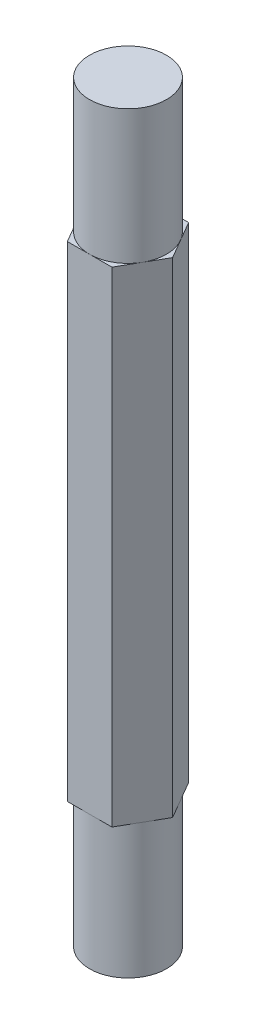
SolidWorks part; units mm, degrees
material "1060 Alloy"
ref_plane "Front Plane" through (0, 0, 0) normal (0, 0, 1) x (1, 0, 0)
ref_plane "Top Plane" through (0, 0, 0) normal (0, 1, 0) x (1, 0, 0)
ref_plane "Right Plane" through (0, 0, 0) normal (1, 0, 0) x (0, 0, -1)
sketch "Sketch1" plane through (0, 0, 0) normal (0, 1, 0) x (1, 0, 0)
  line L1 (1.8204, 3.1823) -> (-1.8458, 3.1677)
  line L2 (-1.8458, 3.1677) -> (-3.6661, -0.0146)
  line L3 (-3.6661, -0.0146) -> (-1.8204, -3.1823)
  line L4 (-1.8204, -3.1823) -> (1.8458, -3.1677)
  line L5 (1.8458, -3.1677) -> (3.6661, 0.0146)
  line L6 (3.6661, 0.0146) -> (1.8204, 3.1823)
  circle A0 centre (0, 0) radius 3.175 construction
  dimension "D1" = 6.35
extrude "Boss-Extrude1" add sketch "Sketch1" along normal blind 40.005
sketch "Sketch2" plane through (0, 40.005, 0) normal (0, 1, 0) x (1, 0, 0)
  circle A0 centre (0, 0) radius 3.175
extrude "Boss-Extrude2" add sketch "Sketch2" along normal blind 11.049
sketch "Sketch3" plane through (0, 0, 0) normal (0, -1, 0) x (-1, 0, 0)
  circle A0 centre (0, 0) radius 3.175
extrude "Boss-Extrude3" add sketch "Sketch3" along normal blind 11.049
